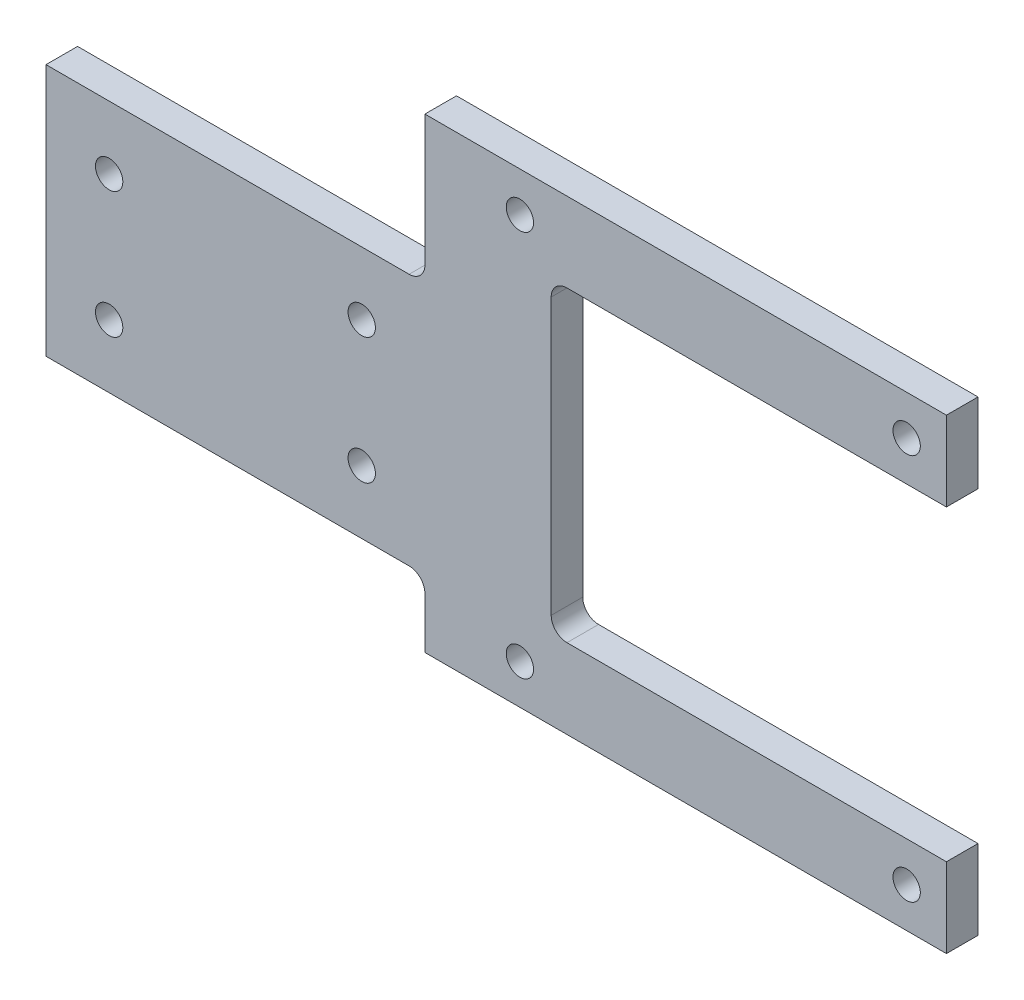
SolidWorks part; units mm, degrees
material "6061-T6 (SS)"
ref_plane "Front" through (0, 0, 0) normal (0, 0, 1) x (1, 0, 0)
ref_plane "Top" through (0, 0, 0) normal (0, 1, 0) x (1, 0, 0)
ref_plane "Right" through (0, 0, 0) normal (1, 0, 0) x (0, 0, -1)
sketch "Sketch1" plane through (0, 0, 0) normal (0, 0, 1) x (1, 0, 0)
  line L0 (38.1, 25.4) -> (38.1, 54.8909)
  line L1 (38.1, 25.4) -> (-38.1, 25.4)
  line L3 (38.1, -25.4) -> (-38.1, -25.4)
  line L4 (-38.1, 25.4) -> (-38.1, -25.4)
  line L5 (38.1, 25.4) -> (-38.1, -25.4) construction
  line L6 (38.1, -25.4) -> (-38.1, 25.4) construction
  line L7 (38.1, 54.8909) -> (142.9909, 54.8909)
  line L8 (142.9909, 54.8909) -> (142.9909, 38.8909)
  line L9 (142.9909, 38.8909) -> (63.5, 38.8909)
  line L10 (63.5, 38.8909) -> (63.5, -22.8909)
  line L11 (63.5, -22.8909) -> (142.9909, -22.8909)
  line L12 (142.9909, -22.8909) -> (142.9909, -38.8909)
  line L13 (142.9909, -38.8909) -> (38.1, -38.8909)
  line L14 (38.1, -38.8909) -> (38.1, -25.4)
  line L15 (142.9909, -38.8909) -> (134.9909, -30.8909) construction
  line L16 (134.9909, -30.8909) -> (142.9909, -22.8909) construction
  line L17 (0, 0) -> (96.1, 8) construction
  line L18 (134.9909, -30.8909) -> (57.2091, 46.8909) construction
  line L19 (134.9909, 46.8909) -> (57.2091, -30.8909) construction
  line L20 (63.5, 38.8909) -> (96.1, 8) construction
  line L21 (96.1, 8) -> (63.5, -22.8909) construction
  line L22 (134.9909, 46.8909) -> (134.9909, 54.8909) construction
  line L23 (134.9909, 46.8909) -> (142.9909, 46.8909) construction
  line L24 (134.9909, 46.8909) -> (134.9909, 38.8909) construction
  line L25 (57.2091, 46.8909) -> (38.1, 46.8909) construction
  line L26 (0, 0) -> (63.5, 0) construction
  circle A0 centre (96.1, 8) radius 55 construction
  point P0 (0, 0)
  point P17 (134.9909, 46.8909)
  point P18 (134.9909, -30.8909)
  point P19 (57.2091, 46.8909)
  point P20 (57.2091, -30.8909)
  dimension "D2" = 110
  dimension "D1" = 50.8
  dimension "D3" = 45
  dimension "D4" = 45
  dimension "D6" = 8
  dimension "D7" = 76.2
  dimension "D8" = 25.4
  dimension "D9" = 58
  dimension "D10" = 8
extrude "Boss-Extrude1" add sketch "Sketch1" along normal blind 6.35
hole_wizard "M5 Clearance Hole1" positions "Sketch3" profile "Sketch4" hole size "M5" standard "ANSI Metric"
sketch "Sketch3" plane through (0, 0, 6.35) normal (0, 0, 1) x (1, 0, 0)
  line L0 (0, 0) -> (96.1, 8) construction
  line L2 (134.9909, -30.8909) -> (57.2091, 46.8909) construction
  line L4 (134.9909, 46.8909) -> (57.2091, -30.8909) construction
  line L6 (63.5, 38.8909) -> (96.1, 8) construction
  line L7 (96.1, 8) -> (63.5, -22.8909) construction
  line L8 (38.1, 25.4) -> (-38.1, 25.4) construction
  line L10 (142.9909, 54.8909) -> (134.9909, 46.8909) construction
  line L11 (134.9909, 46.8909) -> (142.9909, 38.8909) construction
  circle A0 centre (96.1, 8) radius 55 construction
  point P0 (134.9909, 46.8909)
  point P2 (134.9909, -30.8909)
  point P4 (57.2091, 46.8909)
  point P6 (57.2091, -30.8909)
  dimension "D1" = 110
  dimension "D2" = 135
  dimension "D3" = 90
sketch "Sketch4" plane through (134.9909, 46.8909, 6.35) normal (1, 0, 0) x (0, -1, 0)
  line L0 (0, 0) -> (0, 20.4024)
  line L1 (0, 20.4024) -> (2.75, 18.75)
  line L2 (2.75, 18.75) -> (2.75, 0)
  line L5 (2.75, 0) -> (0, 0)
  line L10 (0, 20.4024) -> (-2.75, 18.75) construction
  line L11 (0, -6.35) -> (0, 107.95) construction
  dimension "Hole Dia." = 5.5
  dimension "Hole Depth" = 18.75
  dimension "Drill Angle" = 118
fillet "Fillet1" radius 3.175 4 edges at (63.5, 38.8909, 3.175) (63.5, -22.8909, 3.175) (38.1, -25.4, 3.175) (38.1, 25.4, 3.175)
hole_wizard "M5 Clearance Hole2" positions "Sketch5" profile "Sketch6" hole size "M5" standard "ANSI Metric"
sketch "Sketch5" plane through (0, 0, 6.35) normal (0, 0, 1) x (1, 0, 0)
  line L0 (-25.4, 12.7) -> (25.4, 12.7) construction
  line L1 (25.4, 12.7) -> (25.4, -12.7) construction
  line L2 (25.4, -12.7) -> (-25.4, -12.7) construction
  line L3 (-25.4, -12.7) -> (-25.4, 12.7) construction
  line L5 (34.925, 25.4) -> (-38.1, 25.4) construction
  line L6 (-38.1, -25.4) -> (34.925, -25.4) construction
  line L7 (-38.1, 25.4) -> (-38.1, -25.4) construction
  line L8 (63.5, -19.7159) -> (63.5, 35.7159) construction
  point P0 (-25.4, 12.7)
  point P2 (25.4, 12.7)
  point P4 (25.4, -12.7)
  point P6 (-25.4, -12.7)
  dimension "D1" = 12.7
  dimension "D2" = 12.7
  dimension "D3" = 12.7
  dimension "D4" = 38.1
sketch "Sketch6" plane through (-25.4, 12.7, 6.35) normal (1, 0, 0) x (0, -1, 0)
  line L0 (0, 0) -> (0, 20.4024)
  line L1 (0, 20.4024) -> (2.75, 18.75)
  line L2 (2.75, 18.75) -> (2.75, 0)
  line L5 (2.75, 0) -> (0, 0)
  line L10 (0, 20.4024) -> (-2.75, 18.75) construction
  line L11 (0, -6.35) -> (0, 107.95) construction
  dimension "Hole Dia." = 5.5
  dimension "Hole Depth" = 18.75
  dimension "Drill Angle" = 118
